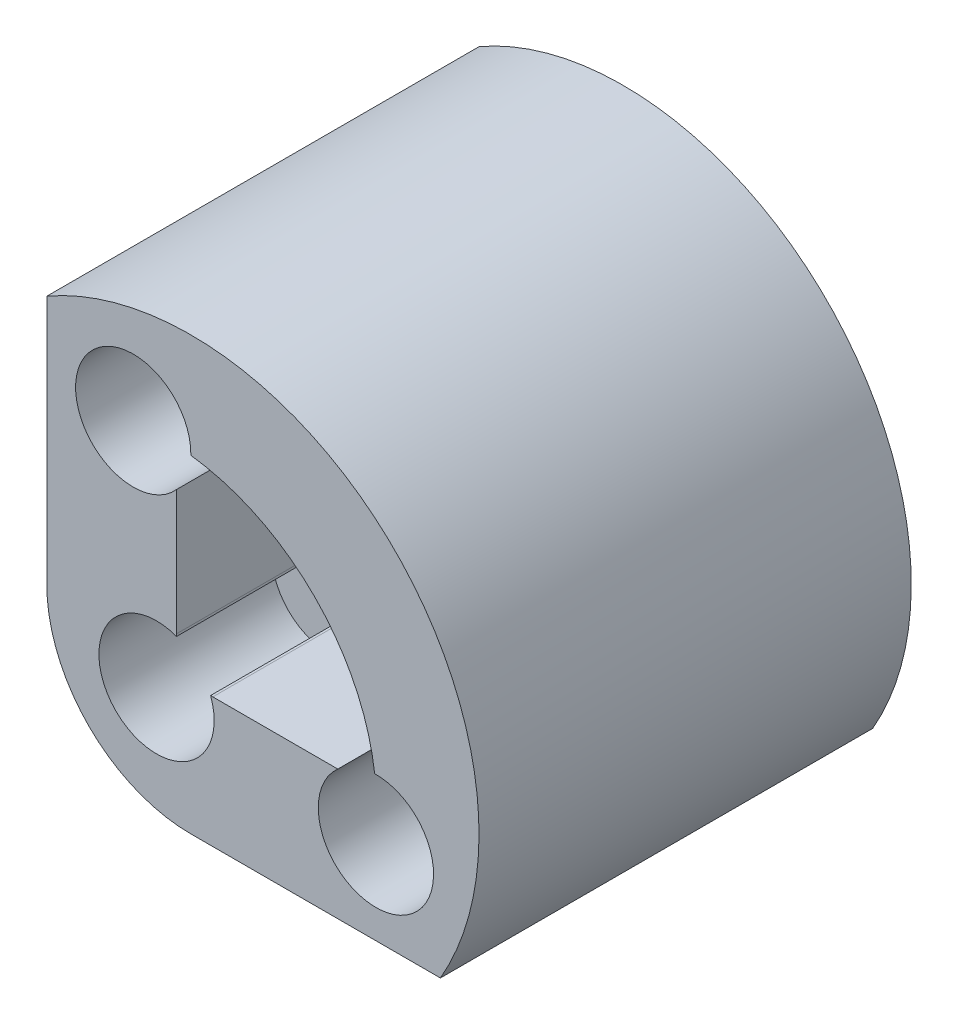
SolidWorks part; units mm, degrees
ref_plane "Plano frontal" through (0, 0, 0) normal (0, 0, 1) x (1, 0, 0)
ref_plane "Plano superior" through (0, 0, 0) normal (0, 1, 0) x (1, 0, 0)
ref_plane "Plano direito" through (0, 0, 0) normal (1, 0, 0) x (0, 0, -1)
sketch "Esboço1" plane through (0, 0, 0) normal (0, 0, 1) x (1, 0, 0)
  line L0 (-7.5, 6.1603) -> (-7.5, -2.5)
  line L1 (6.1603, -7.5) -> (-2.5, -7.5)
  arc A0 (-2.5, -7.5) -> (-7.5, -2.5) centre (-2.5, -2.5) cw
  arc A1 (-7.5, 6.1603) -> (6.1603, -7.5) centre (-2.5, -2.5) cw
extrude "Ressalto-extrusão1" add sketch "Esboço1" along normal blind 15
sketch "Esboço2" plane through (0, 0, 15) normal (0, 0, 1) x (1, 0, 0)
  line L0 (-3, 3.9226) -> (-3, -1.7374)
  line L1 (-7.5, 6.1603) -> (-7.5, -2.5) construction
  line L3 (-1.7374, -3) -> (3.9226, -3)
  line L4 (-2.5, -7.5) -> (6.1603, -7.5) construction
  arc A2 (-3, 3.9226) -> (3.9226, -3) centre (-3.3984, -3.3984) cw
  arc A3 (-3, -1.7374) -> (-1.7374, -3) centre (-1.7374, -1.7374) ccw
  dimension "D3" = 5.66
  dimension "D4" = 4.5
  dimension "D1" = 4.5
  dimension "D2" = 5.66
extrude "Corte-extrusão1" cut sketch "Esboço2" against normal blind 240
sketch "Esboço3" plane through (0, 0, 15) normal (0, 0, 1) x (1, 0, 0)
  point P24 (-5.9543, -3.4518)
sketch "Esboço4" plane through (0, 0, 15) normal (0, 0, 1) x (1, 0, 0)
  circle A3 centre (-3.6908, -3.6908) radius 2
  circle A4 centre (-4.5, 3.9226) radius 2
  circle A5 centre (3.9226, -4.5) radius 2
extrude "Corte-extrusão3" cut sketch "Esboço4" against normal blind 6
sketch "Esboço6" plane through (0, 0, 0) normal (0, 0, -1) x (-1, 0, 0)
  circle A1 centre (4.5, 3.9226) radius 2
  circle A2 centre (-3.9226, -4.5) radius 2
  circle A3 centre (3.6908, -3.6908) radius 2
extrude "Corte-extrusão4" cut sketch "Esboço6" against normal blind 6
